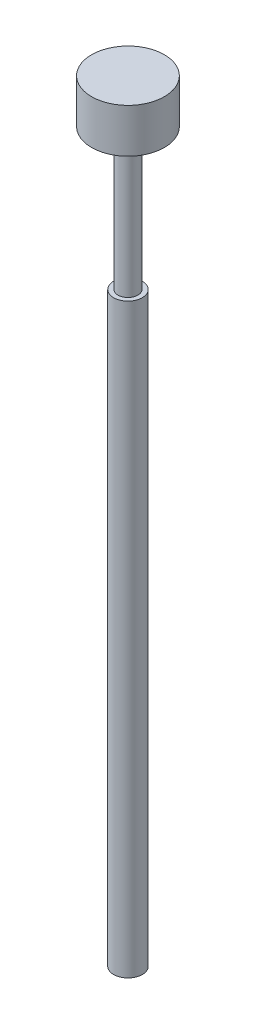
SolidWorks part; units mm, degrees
ref_plane "前视基准面" through (0, 0, 0) normal (0, 0, 1) x (1, 0, 0)
ref_plane "上视基准面" through (0, 0, 0) normal (0, 1, 0) x (1, 0, 0)
ref_plane "右视基准面" through (0, 0, 0) normal (1, 0, 0) x (0, 0, -1)
other "Configuration Table"
sketch "草图2" plane through (0, 0, 0) normal (0, 1, 0) x (1, 0, 0)
  circle A0 centre (0, 0) radius 0.65
  dimension "D1" = 1.3
extrude "凸台-拉伸1" add sketch "草图2" along normal blind 33
sketch "草图3" plane through (0, 33, 0) normal (0, 1, 0) x (1, 0, 0)
  circle A0 centre (0, 0) radius 0.45
  circle A1 centre (0, 0) radius 0.65
  dimension "D1" = 0.9
extrude "切除-拉伸2" cut sketch "草图3" against normal blind 6.4
sketch "草图5" plane through (0, 33, 0) normal (0, 1, 0) x (1, 0, 0)
  circle A0 centre (0, 0) radius 1.65
  dimension "D1" = 3.3
extrude "凸台-拉伸2" add sketch "草图5" along normal blind 2
